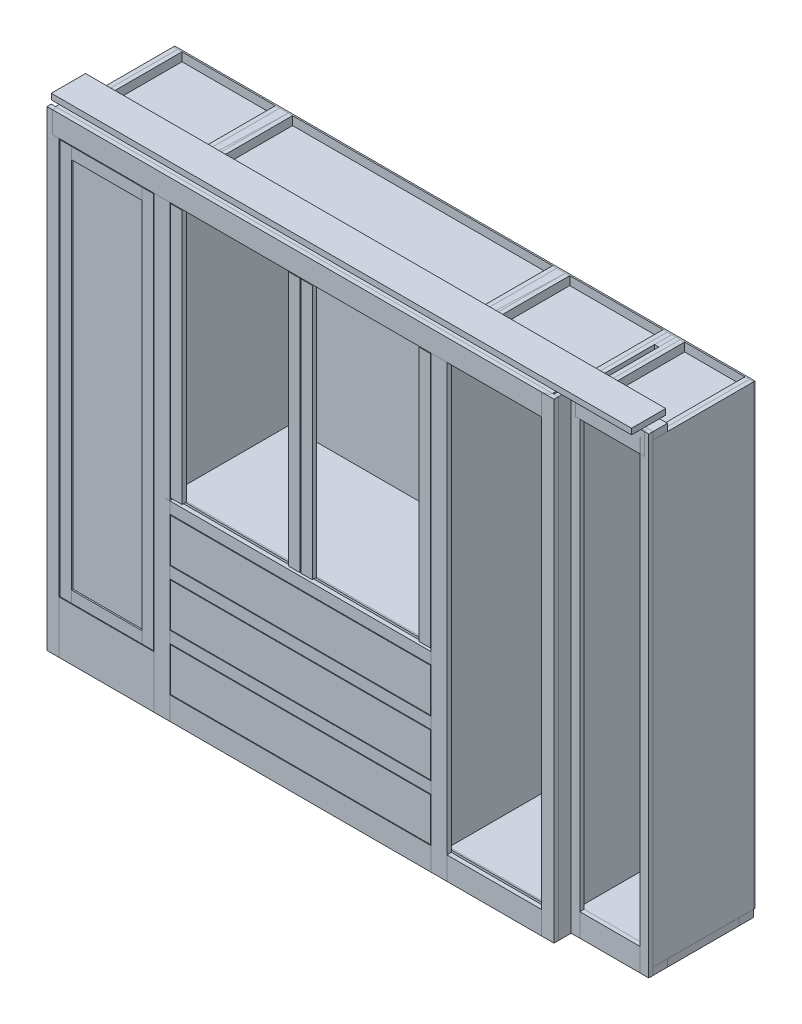
SolidWorks part; units mm, degrees
ref_plane "Front Plane" through (0, 0, 0) normal (0, 0, 1) x (1, 0, 0)
ref_plane "Top Plane" through (0, 0, 0) normal (0, 1, 0) x (1, 0, 0)
ref_plane "Right Plane" through (0, 0, 0) normal (1, 0, 0) x (0, 0, -1)
sketch "Sketch1" plane through (0, 0, 0) normal (0, 0, 1) x (1, 0, 0)
  line L0 (0, 0) -> (0, 1028.7) construction
  line L2 (-254, 19.05) -> (254, 19.05) construction
  line L3 (-254, 19.05) -> (-254, 2038.35) construction
  line L4 (-254, 2038.35) -> (254, 2038.35) construction
  line L5 (254, 19.05) -> (254, 2038.35) construction
  line L6 (-254, 19.05) -> (254, 2038.35) construction
  line L7 (-254, 2038.35) -> (254, 19.05) construction
  line L8 (-254, 2038.35) -> (-234.95, 2038.35)
  line L9 (-254, 2038.35) -> (-254, 19.05)
  line L10 (-254, 19.05) -> (-234.95, 19.05)
  line L11 (-234.95, 2038.35) -> (-234.95, 19.05)
  line L12 (254, 2038.35) -> (215.9, 2038.35)
  line L13 (254, 2038.35) -> (254, 19.05)
  line L14 (254, 19.05) -> (215.9, 19.05)
  line L15 (215.9, 2038.35) -> (215.9, 19.05)
  dimension "D1" = 19.05
  dimension "D3" = 508
  dimension "D4" = 19.05
  dimension "D2" = 2019.3
  dimension "D5" = 38.1
extrude "Boss-Extrude1" add sketch "Sketch1" against normal blind 520.7
sketch "Sketch2" plane through (0, 0, -520.7) normal (0, 0, -1) x (-1, 0, 0)
  line L1 (-215.9, 209.55) -> (-196.85, 209.55)
  line L2 (-215.9, 209.55) -> (-215.9, 19.05)
  line L3 (-215.9, 19.05) -> (-196.85, 19.05)
  line L4 (-196.85, 209.55) -> (-196.85, 19.05)
  line L6 (234.95, 19.05) -> (215.9, 19.05)
  line L7 (234.95, 19.05) -> (234.95, 209.55)
  line L8 (234.95, 209.55) -> (215.9, 209.55)
  line L9 (215.9, 19.05) -> (215.9, 209.55)
  dimension "D1" = 190.5
  dimension "D2" = 19.05
extrude "Boss-Extrude2" add sketch "Sketch2" against normal up to surface (520.7 mm away) separate body up to face at (-244.475, 1028.7, 0)
sketch "Sketch4" plane through (0, 0, -520.7) normal (0, 0, 1) x (1, 0, 0)
  line L1 (215.9, 209.55) -> (-234.95, 209.55)
  line L2 (215.9, 209.55) -> (215.9, 228.6)
  line L3 (215.9, 228.6) -> (-234.95, 228.6)
  line L4 (-234.95, 209.55) -> (-234.95, 228.6)
  dimension "D1" = 19.05
extrude "Boss-Extrude4" add sketch "Sketch4" along normal offset from surface (514.35 mm away) 6.35 separate body up to face at (-244.475, 1028.7, 0)
sketch "Sketch5" plane through (0, 0, -520.7) normal (0, 0, 1) x (1, 0, 0)
  line L1 (215.9, 2038.35) -> (196.85, 2038.35)
  line L2 (215.9, 2038.35) -> (215.9, 2000.25)
  line L3 (215.9, 2000.25) -> (196.85, 2000.25)
  line L4 (196.85, 2038.35) -> (196.85, 2000.25)
  line L5 (-234.95, 2038.35) -> (-215.9, 2038.35)
  line L6 (-234.95, 2038.35) -> (-234.95, 2000.25)
  line L7 (-234.95, 2000.25) -> (-215.9, 2000.25)
  line L8 (-215.9, 2038.35) -> (-215.9, 2000.25)
  dimension "D1" = 19.05
  dimension "D2" = 38.1
extrude "Boss-Extrude5" add sketch "Sketch5" along normal up to surface (520.7 mm away) separate body up to face at (234.95, 1028.7, 0)
sketch "Sketch6" plane through (0, 0, -520.7) normal (0, 0, 1) x (1, 0, 0)
  line L1 (-234.95, 2000.25) -> (215.9, 2000.25)
  line L2 (-234.95, 2000.25) -> (-234.95, 1981.2)
  line L3 (-234.95, 1981.2) -> (215.9, 1981.2)
  line L4 (215.9, 2000.25) -> (215.9, 1981.2)
  dimension "D1" = 19.05
extrude "Boss-Extrude6" add sketch "Sketch6" along normal up to surface (520.7 mm away) separate body up to face at (234.95, 1028.7, 0)
sketch "Sketch61" plane through (0, 0, 0) normal (0, 0, 1) x (1, 0, 0)
  line L0 (215.9, 19.05) -> (254, 19.05) construction
  line L1 (215.9, 2038.35) -> (234.95, 2038.35)
  line L2 (215.9, 2038.35) -> (215.9, 19.05)
  line L3 (215.9, 19.05) -> (234.95, 19.05)
  line L4 (234.95, 2038.35) -> (234.95, 19.05)
extrude "Boss-Extrude48" add sketch "Sketch61" against normal up to next (520.7 mm away) separate body
sketch "Sketch64" plane through (0, 0, -6.35) normal (0, 0, 1) x (1, 0, 0)
  line L0 (215.9, 209.55) -> (-234.95, 209.55) construction
  line L1 (-234.95, 228.6) -> (215.9, 228.6)
  line L2 (-234.95, 228.6) -> (-234.95, 209.55)
  line L3 (-234.95, 209.55) -> (215.9, 209.55)
  line L4 (215.9, 228.6) -> (215.9, 209.55)
extrude "Boss-Extrude50" add sketch "Sketch64" along normal blind 6.35 separate body
sketch "Sketch8" plane through (0, 0, 0) normal (0, 0, 1) x (1, 0, 0)
  line L0 (1695.45, 0) -> (1695.45, 1028.7) construction
  line L1 (254, 19.05) -> (254, 2038.35) construction
  line L2 (1949.45, 19.05) -> (1441.45, 19.05) construction
  line L3 (1949.45, 19.05) -> (1949.45, 2038.35) construction
  line L4 (1949.45, 2038.35) -> (1441.45, 2038.35) construction
  line L5 (1441.45, 19.05) -> (1441.45, 2038.35) construction
  line L6 (1949.45, 19.05) -> (1441.45, 2038.35) construction
  line L7 (1949.45, 2038.35) -> (1441.45, 19.05) construction
  line L8 (3142.9795, 0) -> (-520.5672, 0) construction
  line L10 (1949.45, 2038.35) -> (1930.4, 2038.35)
  line L11 (1949.45, 2038.35) -> (1949.45, 19.05)
  line L12 (1949.45, 19.05) -> (1930.4, 19.05)
  line L13 (1930.4, 2038.35) -> (1930.4, 19.05)
  line L14 (1441.45, 2038.35) -> (1479.55, 2038.35)
  line L15 (1441.45, 2038.35) -> (1441.45, 19.05)
  line L16 (1441.45, 19.05) -> (1479.55, 19.05)
  line L17 (1479.55, 2038.35) -> (1479.55, 19.05)
  dimension "D1" = 19.05
  dimension "D2" = 508
  dimension "D4" = 2019.3
  dimension "D5" = 19.05
  dimension "D3" = 1187.45
  dimension "D6" = 38.1
extrude "Boss-Extrude7" add sketch "Sketch8" against normal blind 520.7 separate body
sketch "Sketch10" plane through (0, 0, -520.7) normal (0, 0, -1) x (-1, 0, 0)
  line L1 (-1498.6, 19.05) -> (-1479.55, 19.05)
  line L2 (-1498.6, 19.05) -> (-1498.6, 79.375)
  line L3 (-1498.6, 79.375) -> (-1479.55, 79.375)
  line L4 (-1479.55, 19.05) -> (-1479.55, 79.375)
  line L5 (-1911.35, 19.05) -> (-1930.4, 19.05)
  line L6 (-1911.35, 19.05) -> (-1911.35, 79.375)
  line L7 (-1911.35, 79.375) -> (-1930.4, 79.375)
  line L8 (-1930.4, 19.05) -> (-1930.4, 79.375)
  dimension "D1" = 19.05
  dimension "D2" = 60.325
  dimension "D3" = 19.05
extrude "Boss-Extrude8" add sketch "Sketch10" against normal up to surface (520.7 mm away) separate body up to face at (1939.925, 1028.7, 0)
sketch "Sketch12" plane through (0, 0, -520.7) normal (0, 0, -1) x (-1, 0, 0)
  line L1 (-1498.6, 2038.35) -> (-1479.55, 2038.35)
  line L2 (-1498.6, 2038.35) -> (-1498.6, 2000.25)
  line L3 (-1498.6, 2000.25) -> (-1479.55, 2000.25)
  line L4 (-1479.55, 2038.35) -> (-1479.55, 2000.25)
  line L5 (-1911.35, 2038.35) -> (-1930.4, 2038.35)
  line L6 (-1911.35, 2038.35) -> (-1911.35, 2000.25)
  line L7 (-1911.35, 2000.25) -> (-1930.4, 2000.25)
  line L8 (-1930.4, 2038.35) -> (-1930.4, 2000.25)
  dimension "D1" = 19.05
  dimension "D4" = 19.05
  dimension "D2" = 38.1
  dimension "D3" = 38.1
extrude "Boss-Extrude9" add sketch "Sketch12" against normal up to surface (520.7 mm away) separate body up to face at (1939.925, 1028.7, 0)
sketch "Sketch13" plane through (0, 0, -520.7) normal (0, 0, -1) x (-1, 0, 0)
  line L0 (-1930.4, 2038.35) -> (-1930.4, 19.05) construction
  line L1 (-1479.55, 79.375) -> (-1930.4, 79.375)
  line L2 (-1479.55, 79.375) -> (-1479.55, 98.425)
  line L3 (-1479.55, 98.425) -> (-1930.4, 98.425)
  line L4 (-1930.4, 79.375) -> (-1930.4, 98.425)
  dimension "D1" = 19.05
extrude "Boss-Extrude10" add sketch "Sketch13" against normal offset from surface (514.35 mm away) 6.35 separate body up to face at (1460.5, 1028.7, 0)
sketch "Sketch14" plane through (0, 0, -520.7) normal (0, 0, -1) x (-1, 0, 0)
  line L0 (-1930.4, 2038.35) -> (-1930.4, 19.05) construction
  line L1 (-1479.55, 2000.25) -> (-1930.4, 2000.25)
  line L2 (-1479.55, 2000.25) -> (-1479.55, 1981.2)
  line L3 (-1479.55, 1981.2) -> (-1930.4, 1981.2)
  line L4 (-1930.4, 2000.25) -> (-1930.4, 1981.2)
  dimension "D1" = 19.05
extrude "Boss-Extrude11" add sketch "Sketch14" against normal up to surface (520.7 mm away) separate body up to face at (1939.925, 1028.7, 0)
sketch "Sketch66" plane through (0, 0, -6.35) normal (0, 0, 1) x (1, 0, 0)
  line L0 (1930.4, 79.375) -> (1479.55, 79.375) construction
  line L1 (1479.55, 98.425) -> (1930.4, 98.425)
  line L2 (1479.55, 98.425) -> (1479.55, 79.375)
  line L3 (1479.55, 79.375) -> (1930.4, 79.375)
  line L4 (1930.4, 98.425) -> (1930.4, 79.375)
extrude "Boss-Extrude52" add sketch "Sketch66" along normal blind 6.35 separate body
sketch "Sketch69" plane through (0, 0, 0) normal (0, 0, 1) x (1, 0, 0)
  line L1 (1479.55, 2038.35) -> (1460.5, 2038.35)
  line L2 (1479.55, 2038.35) -> (1479.55, 19.05)
  line L3 (1479.55, 19.05) -> (1460.5, 19.05)
  line L4 (1460.5, 2038.35) -> (1460.5, 19.05)
extrude "Boss-Extrude55" add sketch "Sketch69" against normal up to next (520.7 mm away) separate body
sketch "Sketch15" plane through (0, 0, -520.7) normal (0, 0, -1) x (-1, 0, 0)
  line L1 (-254, 19.05) -> (-273.05, 19.05)
  line L2 (-254, 19.05) -> (-254, 69.85)
  line L3 (-254, 69.85) -> (-273.05, 69.85)
  line L4 (-273.05, 19.05) -> (-273.05, 69.85)
  line L5 (-1441.45, 19.05) -> (-1422.4, 19.05)
  line L6 (-1441.45, 19.05) -> (-1441.45, 69.85)
  line L7 (-1441.45, 69.85) -> (-1422.4, 69.85)
  line L8 (-1422.4, 19.05) -> (-1422.4, 69.85)
  line L9 (-1441.45, 2038.35) -> (-1422.4, 2038.35)
  line L10 (-1441.45, 2038.35) -> (-1441.45, 2000.25)
  line L11 (-1441.45, 2000.25) -> (-1422.4, 2000.25)
  line L12 (-1422.4, 2038.35) -> (-1422.4, 2000.25)
  line L13 (-254, 2038.35) -> (-273.05, 2038.35)
  line L14 (-254, 2038.35) -> (-254, 2000.25)
  line L15 (-254, 2000.25) -> (-273.05, 2000.25)
  line L16 (-273.05, 2038.35) -> (-273.05, 2000.25)
  dimension "D1" = 19.05
  dimension "D2" = 38.1
  dimension "D3" = 50.8
extrude "Boss-Extrude12" add sketch "Sketch15" against normal up to surface (520.7 mm away) separate body up to face at (1460.5, 1028.7, 0)
sketch "Sketch16" plane through (0, 0, -520.7) normal (0, 0, -1) x (-1, 0, 0)
  line L0 (-254, 19.05) -> (-254, 2038.35) construction
  line L1 (-1441.45, 2000.25) -> (-254, 2000.25)
  line L2 (-1441.45, 2000.25) -> (-1441.45, 1981.2)
  line L3 (-1441.45, 1981.2) -> (-254, 1981.2)
  line L4 (-254, 2000.25) -> (-254, 1981.2)
  line L6 (-1441.45, 69.85) -> (-254, 69.85)
  line L7 (-1441.45, 69.85) -> (-1441.45, 88.9)
  line L8 (-1441.45, 88.9) -> (-254, 88.9)
  line L9 (-254, 69.85) -> (-254, 88.9)
  dimension "D1" = 19.05
  dimension "D2" = 19.05
extrude "Boss-Extrude13" add sketch "Sketch16" against normal up to surface (520.7 mm away) separate body up to face at (1460.5, 1028.7, 0)
sketch "Sketch17" plane through (0, 0, -520.7) normal (0, 0, -1) x (-1, 0, 0)
  line L0 (-254, 19.05) -> (-254, 2038.35) construction
  line L1 (-1441.45, 1981.2) -> (-254, 1981.2) construction
  line L2 (-1441.45, 1981.2) -> (-1441.45, 841.375) construction
  line L3 (-1441.45, 841.375) -> (-254, 841.375) construction
  line L4 (-254, 1981.2) -> (-254, 841.375) construction
  line L6 (-1441.45, 841.375) -> (-254, 841.375)
  line L7 (-1441.45, 841.375) -> (-1441.45, 822.325)
  line L8 (-1441.45, 822.325) -> (-254, 822.325)
  line L9 (-254, 841.375) -> (-254, 822.325)
  line L10 (-254, 88.9) -> (-1441.45, 88.9) construction
  dimension "D2" = 19.05
  dimension "D1" = 733.425
extrude "Boss-Extrude14" add sketch "Sketch17" against normal offset from surface (514.35 mm away) 6.35 separate body up to face at (234.95, 1028.7, 0)
sketch "Sketch65" plane through (0, 0, -6.35) normal (0, 0, 1) x (1, 0, 0)
  line L0 (1441.45, 822.325) -> (1441.45, 841.375) construction
  line L1 (254, 841.375) -> (1441.45, 841.375)
  line L2 (254, 841.375) -> (254, 822.325)
  line L3 (254, 822.325) -> (1441.45, 822.325)
  line L4 (1441.45, 841.375) -> (1441.45, 822.325)
  line L5 (254, 822.325) -> (1441.45, 822.325) construction
extrude "Boss-Extrude51" add sketch "Sketch65" along normal blind 6.35 separate body
sketch "Sketch67" plane through (0, 0, 0) normal (0, 0, 1) x (1, 0, 0)
  line L1 (254, 2038.35) -> (234.95, 2038.35)
  line L2 (254, 2038.35) -> (254, 19.05)
  line L3 (254, 19.05) -> (234.95, 19.05)
  line L4 (234.95, 2038.35) -> (234.95, 19.05)
extrude "Boss-Extrude53" add sketch "Sketch67" against normal up to next (520.7 mm away) separate body
sketch "Sketch68" plane through (0, 0, 0) normal (0, 0, 1) x (1, 0, 0)
  line L0 (1441.45, 19.05) -> (1479.55, 19.05) construction
  line L1 (1441.45, 2038.35) -> (1460.5, 2038.35)
  line L2 (1441.45, 2038.35) -> (1441.45, 19.05)
  line L3 (1441.45, 19.05) -> (1460.5, 19.05)
  line L4 (1460.5, 2038.35) -> (1460.5, 19.05)
extrude "Boss-Extrude54" add sketch "Sketch68" against normal up to next (520.7 mm away) separate body
sketch "Sketch25" plane through (0, 0, -520.7) normal (0, 0, -1) x (-1, 0, 0)
  line L0 (-1949.45, 19.05) -> (-1949.45, 2038.35) construction
  line L1 (-1968.5, 2038.35) -> (-1987.55, 2038.35)
  line L2 (-1968.5, 2038.35) -> (-1968.5, 19.05)
  line L3 (-1968.5, 19.05) -> (-1987.55, 19.05)
  line L4 (-1987.55, 2038.35) -> (-1987.55, 19.05)
  line L5 (-1949.45, 2038.35) -> (-1930.4, 2038.35) construction
  dimension "D1" = 19.05
  dimension "D2" = 19.05
extrude "Boss-Extrude22" add sketch "Sketch25" against normal blind 444.5 separate body
sketch "Sketch26" plane through (0, 0, -520.7) normal (0, 0, 1) x (1, 0, 0)
  line L1 (1987.55, 2038.35) -> (2311.4, 2038.35) construction
  line L2 (1987.55, 2038.35) -> (1987.55, 19.05) construction
  line L3 (1987.55, 19.05) -> (2311.4, 19.05) construction
  line L4 (2311.4, 2038.35) -> (2311.4, 19.05) construction
  line L5 (2311.4, 2038.35) -> (2292.35, 2038.35)
  line L6 (2311.4, 2038.35) -> (2311.4, 19.05)
  line L7 (2311.4, 19.05) -> (2292.35, 19.05)
  line L8 (2292.35, 2038.35) -> (2292.35, 19.05)
  dimension "D3" = 19.05
  dimension "D2" = 2019.3
  dimension "D1" = 323.85
extrude "Boss-Extrude23" add sketch "Sketch26" along normal blind 444.5 separate body
sketch "Sketch27" plane through (0, 0, -520.7) normal (0, 0, -1) x (-1, 0, 0)
  line L1 (-1987.55, 2038.35) -> (-2006.6, 2038.35)
  line L2 (-1987.55, 2038.35) -> (-1987.55, 2000.25)
  line L3 (-1987.55, 2000.25) -> (-2006.6, 2000.25)
  line L4 (-2006.6, 2038.35) -> (-2006.6, 2000.25)
  line L5 (-2292.35, 2038.35) -> (-2273.3, 2038.35)
  line L6 (-2292.35, 2038.35) -> (-2292.35, 2000.25)
  line L7 (-2292.35, 2000.25) -> (-2273.3, 2000.25)
  line L8 (-2273.3, 2038.35) -> (-2273.3, 2000.25)
  line L9 (-1987.55, 19.05) -> (-2006.6, 19.05)
  line L10 (-1987.55, 19.05) -> (-1987.55, 69.85)
  line L11 (-1987.55, 69.85) -> (-2006.6, 69.85)
  line L12 (-2006.6, 19.05) -> (-2006.6, 69.85)
  line L13 (-2292.35, 19.05) -> (-2273.3, 19.05)
  line L14 (-2292.35, 19.05) -> (-2292.35, 69.85)
  line L15 (-2292.35, 69.85) -> (-2273.3, 69.85)
  line L16 (-2273.3, 19.05) -> (-2273.3, 69.85)
  dimension "D1" = 19.05
  dimension "D2" = 38.1
  dimension "D3" = 50.8
extrude "Boss-Extrude24" add sketch "Sketch27" against normal up to surface (444.5 mm away) separate body up to face at (2301.875, 1028.7, -76.2)
sketch "Sketch28" plane through (0, 0, -520.7) normal (0, 0, -1) x (-1, 0, 0)
  line L0 (-2292.35, 2038.35) -> (-2292.35, 19.05) construction
  line L1 (-1987.55, 69.85) -> (-2292.35, 69.85)
  line L2 (-1987.55, 69.85) -> (-1987.55, 88.9)
  line L3 (-1987.55, 88.9) -> (-2292.35, 88.9)
  line L4 (-2292.35, 69.85) -> (-2292.35, 88.9)
  line L6 (-1987.55, 2000.25) -> (-2292.35, 2000.25)
  line L7 (-1987.55, 2000.25) -> (-1987.55, 1981.2)
  line L8 (-1987.55, 1981.2) -> (-2292.35, 1981.2)
  line L9 (-2292.35, 2000.25) -> (-2292.35, 1981.2)
  dimension "D1" = 19.05
extrude "Boss-Extrude25" add sketch "Sketch28" against normal up to surface (444.5 mm away) separate body up to face at (2301.875, 1028.7, -76.2)
sketch "Sketch20" plane through (0, 0, 0) normal (0, 0, 1) x (1, 0, 0)
  line L1 (-254, 2038.35) -> (-273.05, 2038.35)
  line L2 (-254, 2038.35) -> (-254, 19.05)
  line L3 (-254, 19.05) -> (-273.05, 19.05)
  line L4 (-273.05, 2038.35) -> (-273.05, 19.05)
  dimension "D1" = 19.05
extrude "Boss-Extrude17" add sketch "Sketch20" against normal blind 63.5 separate body
sketch "Sketch21" plane through (0, 0, 0) normal (0, 0, 1) x (1, 0, 0)
  line L0 (-234.95, 19.05) -> (-234.95, 2038.35) construction
  line L1 (-219.075, 2070.1) -> (-273.05, 2070.1)
  line L2 (-219.075, 2070.1) -> (-219.075, -12.7)
  line L3 (-219.075, -12.7) -> (-273.05, -12.7)
  line L4 (-273.05, 2070.1) -> (-273.05, -12.7)
  line L8 (-254, 19.05) -> (-234.95, 19.05) construction
  line L9 (-234.95, 2038.35) -> (-215.9, 2038.35) construction
  dimension "D1" = 15.875
  dimension "D2" = 53.975
  dimension "D3" = 31.75
  dimension "D4" = 31.75
extrude "Boss-Extrude18" add sketch "Sketch21" along normal blind 19.05 separate body
sketch "Sketch22" plane through (0, 0, 0) normal (0, 0, 1) x (1, 0, 0)
  line L0 (234.95, 1959.776) -> (234.95, 1827.9449) construction
  line L1 (254, 2038.35) -> (215.9, 2038.35) construction
  line L2 (1460.5, 2082.8) -> (1460.5, -47917.2) construction
  line L3 (1479.55, 2038.35) -> (1441.45, 2038.35) construction
  line L4 (1949.45, 2082.8) -> (1949.45, 52082.8) construction
  line L5 (1930.4, 2038.35) -> (1930.4, 19.05) construction
  line L6 (-219.075, -12.7) -> (-219.075, 2070.1) construction
  line L7 (200.025, -12.7) -> (269.875, -12.7)
  line L8 (200.025, -12.7) -> (200.025, 2070.1)
  line L9 (200.025, 2070.1) -> (269.875, 2070.1)
  line L10 (269.875, -12.7) -> (269.875, 2070.1)
  line L11 (200.025, -12.7) -> (269.875, 2070.1) construction
  line L12 (200.025, 2070.1) -> (269.875, -12.7) construction
  line L13 (1425.575, -12.7) -> (1495.425, -12.7)
  line L14 (1425.575, -12.7) -> (1425.575, 2070.1)
  line L15 (1425.575, 2070.1) -> (1495.425, 2070.1)
  line L16 (1495.425, -12.7) -> (1495.425, 2070.1)
  line L17 (1425.575, -12.7) -> (1495.425, 2070.1) construction
  line L18 (1425.575, 2070.1) -> (1495.425, -12.7) construction
  line L19 (1914.525, -12.7) -> (1968.5, -12.7)
  line L20 (1914.525, -12.7) -> (1914.525, 2070.1)
  line L21 (1914.525, 2070.1) -> (1968.5, 2070.1)
  line L22 (1968.5, -12.7) -> (1968.5, 2070.1)
  line L23 (1914.525, -12.7) -> (1968.5, 2070.1) construction
  line L24 (1914.525, 2070.1) -> (1968.5, -12.7) construction
  line L27 (215.9, 19.05) -> (254, 19.05) construction
  line L28 (1949.45, 19.05) -> (1949.45, 2038.35) construction
  line L29 (1930.4, 2038.35) -> (1911.35, 2038.35) construction
  point P6 (1460.5, 2038.35)
  point P12 (234.95, 1028.7)
  point P17 (1460.5, 1028.7)
  point P22 (1941.5125, 1028.7)
  point P27 (234.95, 2038.35)
  dimension "D1" = 69.85
  dimension "D3" = 31.75
  dimension "D5" = 31.75
  dimension "D4" = 15.875
  dimension "D6" = 53.975
extrude "Boss-Extrude19" add sketch "Sketch22" along normal blind 19.05 separate body
sketch "Sketch23" plane through (0, 0, 0) normal (0, 0, 1) x (1, 0, 0)
  line L1 (-246.1329, -12.7) -> (234.95, -12.7)
  line L2 (-246.1329, -12.7) -> (-246.1329, 219.075)
  line L3 (-246.1329, 219.075) -> (234.95, 219.075)
  line L4 (234.95, -12.7) -> (234.95, 219.075)
  line L5 (-234.95, 228.6) -> (215.9, 228.6) construction
  line L8 (200.025, -12.7) -> (269.875, -12.7) construction
  dimension "D1" = 9.525
extrude "Boss-Extrude20" add sketch "Sketch23" along normal blind 19.05 separate body
sketch "Sketch24" plane through (0, 0, 0) normal (0, 0, 1) x (1, 0, 0)
  line L0 (200.025, -12.7) -> (269.875, -12.7) construction
  line L1 (234.95, -12.7) -> (1949.45, -12.7)
  line L2 (234.95, -12.7) -> (234.95, 88.9)
  line L3 (234.95, 88.9) -> (1949.45, 88.9)
  line L4 (1949.45, -12.7) -> (1949.45, 88.9)
  line L5 (1949.45, 19.05) -> (1949.45, 2038.35) construction
  line L6 (863.6, -193.55) -> (863.6, 49806.45) construction
  line L7 (1941.5125, 1974.85) -> (-248.3733, 1974.85)
  line L8 (1941.5125, 1974.85) -> (1941.5125, 2070.1)
  line L9 (1941.5125, 2070.1) -> (-248.3733, 2070.1)
  line L10 (-248.3733, 1974.85) -> (-248.3733, 2070.1)
  line L11 (1968.5, 2070.1) -> (1914.525, 2070.1) construction
  line L12 (-746, 723.9) -> (49254, 723.9) construction
  line L13 (1479.55, 1981.2) -> (1930.4, 1981.2) construction
  line L15 (1460.5, 1082.8) -> (1460.5, 51082.8) construction
  line L16 (234.95, 781.05) -> (1460.5, 781.05)
  line L17 (234.95, 781.05) -> (234.95, 831.85)
  line L18 (234.95, 831.85) -> (1460.5, 831.85)
  line L19 (1460.5, 781.05) -> (1460.5, 831.85)
  line L20 (234.95, 781.05) -> (1460.5, 831.85) construction
  line L21 (234.95, 831.85) -> (1460.5, 781.05) construction
  line L22 (1479.55, 2038.35) -> (1441.45, 2038.35) construction
  line L23 (234.95, 1082.8) -> (234.95, 51082.8) construction
  line L24 (254, 2038.35) -> (215.9, 2038.35) construction
  point P12 (1941.5125, 2070.1)
  point P21 (602.7923, 796.2974)
  point P35 (1460.5, 2038.35)
  point P40 (234.95, 2038.35)
  dimension "D1" = 101.6
  dimension "D2" = 0
  dimension "D3" = 95.25
  dimension "D4" = 50.8
  dimension "D6" = 6.35
  dimension "D7" = 692.15
extrude "Boss-Extrude21" add sketch "Sketch24" along normal blind 19.05 separate body
sketch "Sketch29" plane through (0, 0, -76.2) normal (0, 0, 1) x (1, 0, 0)
  line L0 (1914.525, -12.7) -> (1968.5, -12.7) construction
  line L1 (1941.5125, 2070.1) -> (-248.3733, 2070.1) construction
  line L6 (2311.4, 2070.1) -> (2273.3, 2070.1)
  line L7 (2311.4, 2070.1) -> (2311.4, -12.7)
  line L8 (2311.4, -12.7) -> (2273.3, -12.7)
  line L9 (2273.3, 2070.1) -> (2273.3, -12.7)
  line L10 (1968.5, 2070.1) -> (2006.6, 2070.1)
  line L11 (1968.5, 2070.1) -> (1968.5, -12.7)
  line L12 (1968.5, -12.7) -> (2006.6, -12.7)
  line L13 (2006.6, 2070.1) -> (2006.6, -12.7)
  dimension "D1" = 38.1
extrude "Boss-Extrude26" add sketch "Sketch29" along normal blind 19.05 separate body
sketch "Sketch30" plane through (0, 0, -76.2) normal (0, 0, 1) x (1, 0, 0)
  line L0 (2292.35, 1981.2) -> (1987.55, 1981.2) construction
  line L1 (1987.55, 1974.85) -> (2292.35, 1974.85)
  line L2 (1987.55, 1974.85) -> (1987.55, 2070.1)
  line L3 (1987.55, 2070.1) -> (2292.35, 2070.1)
  line L4 (2292.35, 1974.85) -> (2292.35, 2070.1)
  line L5 (1987.55, 88.9) -> (2292.35, 88.9)
  line L6 (1987.55, 88.9) -> (1987.55, -12.7)
  line L7 (1987.55, -12.7) -> (2292.35, -12.7)
  line L8 (2292.35, 88.9) -> (2292.35, -12.7)
  line L11 (2273.3, -12.7) -> (2311.4, -12.7) construction
  line L12 (2006.6, 2070.1) -> (1968.5, 2070.1) construction
  line L13 (2311.4, 2070.1) -> (2273.3, 2070.1) construction
  point P17 (2292.35, -12.7)
  point P21 (1987.55, 2070.1)
  point P22 (2292.35, 2070.1)
  dimension "D3" = 6.35
extrude "Boss-Extrude27" add sketch "Sketch30" along normal blind 19.05 separate body
sketch "Sketch33" plane through (0, 0, 0) normal (0, 0, 1) x (1, 0, 0)
  line L0 (-248.3733, 1974.85) -> (1941.5125, 1974.85) construction
  line L1 (-219.075, 1974.85) -> (200.025, 1974.85) construction
  line L2 (-219.075, 1974.85) -> (-219.075, 219.075) construction
  line L3 (-219.075, 219.075) -> (200.025, 219.075) construction
  line L4 (200.025, 1974.85) -> (200.025, 219.075) construction
  line L5 (-219.075, -12.7) -> (-219.075, 2070.1) construction
  line L6 (200.025, 2070.1) -> (200.025, -12.7) construction
  line L7 (234.95, 219.075) -> (-246.1329, 219.075) construction
  line L8 (-215.9, 1971.675) -> (196.85, 1971.675) construction
  line L9 (196.85, 1971.675) -> (196.85, 222.25) construction
  line L10 (-215.9, 222.25) -> (196.85, 222.25) construction
  line L11 (-215.9, 1971.675) -> (-215.9, 222.25) construction
  line L13 (-215.9, 1971.675) -> (-165.1, 1971.675)
  line L14 (-215.9, 1971.675) -> (-215.9, 222.25)
  line L15 (-215.9, 222.25) -> (-165.1, 222.25)
  line L16 (-165.1, 1971.675) -> (-165.1, 222.25)
  line L17 (196.85, 222.25) -> (146.05, 222.25)
  line L18 (196.85, 222.25) -> (196.85, 1971.675)
  line L19 (196.85, 1971.675) -> (146.05, 1971.675)
  line L20 (146.05, 222.25) -> (146.05, 1971.675)
  dimension "D2" = 50.8
  dimension "D1" = 3.175
extrude "Boss-Extrude29" add sketch "Sketch33" along normal blind 19.05 separate body
sketch "Sketch34" plane through (0, 0, 0) normal (0, 0, 1) x (1, 0, 0)
  line L0 (146.05, 222.25) -> (196.85, 222.25) construction
  line L1 (-177.8, 1971.675) -> (158.75, 1971.675)
  line L2 (-177.8, 1971.675) -> (-177.8, 1920.875)
  line L3 (-177.8, 1920.875) -> (158.75, 1920.875)
  line L4 (158.75, 1971.675) -> (158.75, 1920.875)
  line L6 (-177.8, 222.25) -> (158.75, 222.25)
  line L7 (-177.8, 222.25) -> (-177.8, 273.05)
  line L8 (-177.8, 273.05) -> (158.75, 273.05)
  line L9 (158.75, 222.25) -> (158.75, 273.05)
  line L10 (-165.1, 222.25) -> (-165.1, 1971.675) construction
  line L11 (146.05, 1971.675) -> (146.05, 222.25) construction
  line L12 (-165.1, 1971.675) -> (-215.9, 1971.675) construction
  dimension "D1" = 50.8
  dimension "D2" = 12.7
  dimension "D3" = 12.7
extrude "Boss-Extrude30" add sketch "Sketch34" along normal blind 19.05 separate body
sketch "Sketch36" plane through (0, 1971.675, 0) normal (0, 1, 0) x (1, 0, 0)
  line L0 (-165.1, -19.05) -> (-165.1, 0) construction
  line L1 (-165.1, -6.35) -> (-177.8, -6.35)
  line L2 (-165.1, -6.35) -> (-165.1, -12.7)
  line L3 (-165.1, -12.7) -> (-177.8, -12.7)
  line L4 (-177.8, -6.35) -> (-177.8, -12.7)
  line L5 (-1168.275, -9.525) -> (48831.725, -9.525) construction
  line L6 (-9.525, -19.05) -> (-9.525, 0) construction
  line L7 (158.75, -19.05) -> (-177.8, -19.05) construction
  line L8 (158.75, 0) -> (-177.8, 0) construction
  line L9 (158.75, -6.35) -> (158.75, -12.7)
  line L10 (146.05, -12.7) -> (158.75, -12.7)
  line L11 (146.05, -6.35) -> (146.05, -12.7)
  line L12 (146.05, -6.35) -> (158.75, -6.35)
  point P9 (-165.1, -9.525)
  dimension "D2" = 12.7
  dimension "D1" = 6.35
extrude "Cut-Extrude1" cut sketch "Sketch36" against normal through all
sketch "Sketch37" plane through (0, 1971.675, 0) normal (0, 1, 0) x (1, 0, 0)
  line L1 (-165.1, -6.35) -> (-177.8, -6.35)
  line L2 (-165.1, -6.35) -> (-165.1, 0)
  line L3 (-165.1, 0) -> (-177.8, 0)
  line L4 (-177.8, -6.35) -> (-177.8, 0)
  line L6 (-165.1, -12.7) -> (-177.8, -12.7)
  line L7 (-165.1, -12.7) -> (-165.1, -19.05)
  line L8 (-165.1, -19.05) -> (-177.8, -19.05)
  line L9 (-177.8, -12.7) -> (-177.8, -19.05)
  line L10 (-177.8, -6.35) -> (-177.8, -12.7) construction
  line L12 (158.75, 0) -> (-177.8, 0) construction
  line L13 (158.75, -19.05) -> (-177.8, -19.05) construction
  line L14 (-9.525, -19.05) -> (-9.525, 0) construction
  line L15 (158.75, -12.7) -> (158.75, -19.05)
  line L16 (146.05, -19.05) -> (158.75, -19.05)
  line L17 (146.05, -12.7) -> (146.05, -19.05)
  line L18 (146.05, -12.7) -> (158.75, -12.7)
  line L19 (158.75, -6.35) -> (158.75, 0)
  line L20 (146.05, 0) -> (158.75, 0)
  line L21 (146.05, -6.35) -> (146.05, 0)
  line L22 (146.05, -6.35) -> (158.75, -6.35)
extrude "Cut-Extrude2" cut sketch "Sketch37" against normal through all
sketch "Sketch39" plane through (-177.8, 0, 0) normal (-1, 0, 0) x (0, 0, 1)
  line L0 (6.35, 1920.875) -> (6.35, 1971.675) construction
  line L1 (12.7, 1920.875) -> (6.35, 1920.875)
  line L2 (12.7, 1920.875) -> (12.7, 1933.575)
  line L3 (12.7, 1933.575) -> (6.35, 1933.575)
  line L4 (6.35, 1920.875) -> (6.35, 1933.575)
  line L5 (6.35, 222.25) -> (6.35, 273.05) construction
  line L6 (12.7, 273.05) -> (6.35, 273.05)
  line L7 (12.7, 273.05) -> (12.7, 260.35)
  line L8 (12.7, 260.35) -> (6.35, 260.35)
  line L9 (6.35, 273.05) -> (6.35, 260.35)
  dimension "D2" = 12.7
  dimension "D1" = 12.7
extrude "Cut-Extrude3" cut sketch "Sketch39" against normal through all
sketch "Sketch40" plane through (0, 0, 6.35) normal (0, 0, -1) x (-1, 0, 0)
  line L1 (177.8, 1933.575) -> (-158.75, 1933.575)
  line L2 (177.8, 1933.575) -> (177.8, 260.35)
  line L3 (177.8, 260.35) -> (-158.75, 260.35)
  line L4 (-158.75, 1933.575) -> (-158.75, 260.35)
extrude "Boss-Extrude31" add sketch "Sketch40" against normal up to surface (6.35 mm away) separate body up to face at (-9.525, 266.7, 12.7)
sketch "Sketch41" plane through (0, 0, -520.7) normal (0, 0, -1) x (-1, 0, 0)
  line L1 (254, 2038.35) -> (-2311.4, 2038.35)
  line L2 (254, 2038.35) -> (254, 19.05)
  line L3 (254, 19.05) -> (-2311.4, 19.05)
  line L4 (-2311.4, 2038.35) -> (-2311.4, 19.05)
  line L5 (-2311.4, 19.05) -> (-2311.4, 2038.35) construction
  line L6 (234.95, 2038.35) -> (254, 2038.35) construction
  line L7 (254, 2038.35) -> (254, 19.05) construction
extrude "Boss-Extrude32" add sketch "Sketch41" along normal blind 6.35 separate body
sketch "Sketch42" plane through (0, 2038.35, 0) normal (0, 1, 0) x (1, 0, 0)
  line L2 (-254, 0) -> (1943.1, 0)
  line L3 (-254, 0) -> (-254, 63.5)
  line L4 (-254, 63.5) -> (1943.1, 63.5)
  line L6 (2311.4, 76.2) -> (1447.8, 76.2)
  line L7 (2311.4, 76.2) -> (2311.4, 139.7)
  line L8 (2311.4, 139.7) -> (1447.8, 139.7)
  line L9 (1447.8, 76.2) -> (1447.8, 139.7)
  line L10 (1943.1, 0) -> (1943.1, 63.5)
  dimension "D1" = 863.6
  dimension "D2" = 2197.1
  dimension "D3" = 63.5
extrude "Boss-Extrude33" add sketch "Sketch42" along normal blind 31.75 separate body
sketch "Sketch43" plane through (0, 0, 0) normal (0, 0, 1) x (1, 0, 0)
  line L0 (269.875, -12.7) -> (269.875, 2070.1) construction
  line L1 (269.875, 1974.85) -> (1425.575, 1974.85) construction
  line L2 (269.875, 1974.85) -> (269.875, 841.375) construction
  line L3 (269.875, 841.375) -> (1425.575, 841.375) construction
  line L4 (1425.575, 1974.85) -> (1425.575, 841.375) construction
  line L5 (-248.3733, 1974.85) -> (1941.5125, 1974.85) construction
  line L6 (254, 841.375) -> (1441.45, 841.375) construction
  line L7 (1425.575, 2070.1) -> (1425.575, -12.7) construction
  line L8 (273.05, 1971.675) -> (273.05, 844.55) construction
  line L9 (273.05, 844.55) -> (1422.4, 844.55) construction
  line L10 (1422.4, 1971.675) -> (1422.4, 844.55) construction
  line L11 (273.05, 1971.675) -> (1422.4, 1971.675) construction
  line L13 (1422.4, 1971.675) -> (1371.6, 1971.675)
  line L14 (1422.4, 1971.675) -> (1422.4, 844.55)
  line L15 (1422.4, 844.55) -> (1371.6, 844.55)
  line L16 (1371.6, 1971.675) -> (1371.6, 844.55)
  line L17 (273.05, 1971.675) -> (323.85, 1971.675)
  line L18 (273.05, 1971.675) -> (273.05, 844.55)
  line L19 (273.05, 844.55) -> (323.85, 844.55)
  line L20 (323.85, 1971.675) -> (323.85, 844.55)
  dimension "D2" = 50.8
  dimension "D1" = 3.175
extrude "Boss-Extrude34" add sketch "Sketch43" along normal blind 19.05 separate body
sketch "Sketch44" plane through (0, 0, 0) normal (0, 0, 1) x (1, 0, 0)
  line L0 (847.725, -193.55) -> (847.725, 49806.45) construction
  line L1 (1460.5, 831.85) -> (234.95, 831.85) construction
  line L4 (849.3125, -193.55) -> (849.3125, 49806.45) construction
  line L5 (846.1375, -193.55) -> (846.1375, 49806.45) construction
  line L7 (323.85, 1971.675) -> (1371.6, 1971.675) construction
  line L8 (323.85, 1971.675) -> (323.85, 844.55) construction
  line L9 (323.85, 844.55) -> (1371.6, 844.55) construction
  line L10 (1371.6, 1971.675) -> (1371.6, 844.55) construction
  line L11 (846.1375, 1971.675) -> (795.3375, 1971.675)
  line L12 (846.1375, 1971.675) -> (846.1375, 844.55)
  line L13 (846.1375, 844.55) -> (795.3375, 844.55)
  line L14 (795.3375, 1971.675) -> (795.3375, 844.55)
  line L15 (849.3125, 1971.675) -> (900.1125, 1971.675)
  line L16 (849.3125, 1971.675) -> (849.3125, 844.55)
  line L17 (849.3125, 844.55) -> (900.1125, 844.55)
  line L18 (900.1125, 1971.675) -> (900.1125, 844.55)
  point P5 (847.725, 831.85)
  dimension "D3" = 50.8
extrude "Boss-Extrude35" add sketch "Sketch44" along normal blind 19.05 separate body
sketch "Sketch48" plane through (0, 0, 0) normal (0, 0, 1) x (1, 0, 0)
  line L1 (1949.45, 2070.1) -> (1968.5, 2070.1)
  line L2 (1949.45, 2070.1) -> (1949.45, -12.7)
  line L3 (1949.45, -12.7) -> (1968.5, -12.7)
  line L4 (1968.5, 2070.1) -> (1968.5, -12.7)
  dimension "D1" = 19.05
extrude "Boss-Extrude38" add sketch "Sketch48" against normal offset from surface (152.4 mm away) 76.2 separate body up to face at (1978.025, 1028.7, -76.2) offset beyond the face yes
sketch "Sketch49" plane through (0, 0, -520.7) normal (0, 0, -1) x (-1, 0, 0)
  line L0 (-2311.4, 19.05) -> (254, 19.05) construction
  line L1 (-1949.45, 2038.35) -> (-1968.5, 2038.35)
  line L2 (-1949.45, 2038.35) -> (-1949.45, 19.05)
  line L3 (-1949.45, 19.05) -> (-1968.5, 19.05)
  line L4 (-1968.5, 2038.35) -> (-1968.5, 19.05)
  line L5 (-1987.55, 19.05) -> (-1968.5, 19.05) construction
  dimension "D1" = 19.05
extrude "Boss-Extrude39" add sketch "Sketch49" against normal blind 76.2 separate body
sketch "Sketch50" plane through (0, 2070.1, 0) normal (0, 1, 0) x (1, 0, 0)
  line L0 (1949.45, 152.4) -> (1949.45, 0) construction
  line L1 (1968.5, 152.4) -> (1949.45, 152.4)
  line L2 (1968.5, 152.4) -> (1968.5, 76.2)
  line L3 (1968.5, 76.2) -> (1949.45, 76.2)
  line L4 (1949.45, 152.4) -> (1949.45, 76.2)
extrude "Cut-Extrude5" cut sketch "Sketch50" against normal up to surface (31.75 mm away) up to face at (1978.025, 2038.35, -298.45)
sketch "Sketch58" plane through (0, -12.7, 0) normal (0, -1, 0) x (1, 0, 0)
  line L0 (1968.5, -152.4) -> (1968.5, 0) construction
  line L1 (1968.5, -76.2) -> (1949.45, -76.2)
  line L2 (1968.5, -76.2) -> (1968.5, -152.4)
  line L3 (1968.5, -152.4) -> (1949.45, -152.4)
  line L4 (1949.45, -76.2) -> (1949.45, -152.4)
extrude "Cut-Extrude6" cut sketch "Sketch58" against normal up to surface (31.75 mm away) up to face at (1978.025, 19.05, -298.45)
sketch "Sketch46" plane through (0, 19.05, 0) normal (0, -1, 0) x (1, 0, 0)
  line L1 (-254, -520.7) -> (1943.1, -520.7)
  line L2 (-254, -520.7) -> (-254, -457.2)
  line L3 (-254, -457.2) -> (1943.1, -457.2)
  line L4 (1943.1, -520.7) -> (1943.1, -457.2)
  line L5 (1441.45, 0) -> (254, 0) construction
  line L6 (1943.1, 0) -> (-254, 0)
  line L7 (1943.1, 0) -> (1943.1, -63.5)
  line L8 (1943.1, -63.5) -> (-254, -63.5)
  line L9 (-254, 0) -> (-254, -63.5)
  dimension "D1" = 63.5
  dimension "D2" = 63.5
  dimension "D3" = 2197.1
extrude "Boss-Extrude36" add sketch "Sketch46" along normal blind 31.75 separate body
sketch "Sketch47" plane through (0, 19.05, 0) normal (0, -1, 0) x (1, 0, 0)
  line L0 (1943.1, -457.2) -> (-254, -457.2) construction
  line L1 (-203.2, -63.5) -> (-139.7, -63.5)
  line L2 (-203.2, -63.5) -> (-203.2, -457.2)
  line L3 (-203.2, -457.2) -> (-139.7, -457.2)
  line L4 (-139.7, -63.5) -> (-139.7, -457.2)
  line L5 (317.5, -63.5) -> (381, -63.5)
  line L6 (1943.1, -63.5) -> (1879.6, -63.5)
  line L7 (1943.1, -63.5) -> (1943.1, -457.2)
  line L8 (1943.1, -457.2) -> (1879.6, -457.2)
  line L9 (1879.6, -63.5) -> (1879.6, -457.2)
  line L10 (317.5, -63.5) -> (317.5, -457.2)
  line L11 (317.5, -457.2) -> (381, -457.2)
  line L12 (381, -63.5) -> (381, -457.2)
  line L13 (1320.8, -63.5) -> (1384.3, -63.5)
  line L14 (1320.8, -63.5) -> (1320.8, -457.2)
  line L15 (1320.8, -457.2) -> (1384.3, -457.2)
  line L16 (1384.3, -63.5) -> (1384.3, -457.2)
  line L17 (1943.1, -457.2) -> (-254, -457.2) construction
  line L18 (-254, -457.2) -> (-254, -520.7) construction
  line L19 (-254, -63.5) -> (1943.1, -63.5) construction
  dimension "D1" = 63.5
  dimension "D2" = 63.5
  dimension "D3" = 50.8
  dimension "D5" = 495.3
  dimension "D6" = 939.8
extrude "Boss-Extrude37" add sketch "Sketch47" along normal blind 31.75 separate body
sketch "Sketch59" plane through (0, 19.05, 0) normal (0, 1, 0) x (1, 0, 0)
  line L1 (1949.45, 76.2) -> (2311.4, 76.2)
  line L2 (1949.45, 76.2) -> (1949.45, 139.7)
  line L3 (1949.45, 139.7) -> (2311.4, 139.7)
  line L4 (2311.4, 76.2) -> (2311.4, 139.7)
  line L6 (2311.4, 76.2) -> (2311.4, 520.7) construction
  line L7 (1968.5, 520.7) -> (1949.45, 520.7) construction
  line L8 (1949.45, 520.7) -> (2311.4, 520.7)
  line L9 (1949.45, 520.7) -> (1949.45, 457.2)
  line L10 (1949.45, 457.2) -> (2311.4, 457.2)
  line L11 (2311.4, 520.7) -> (2311.4, 457.2)
  line L12 (2311.4, 520.7) -> (-254, 520.7) construction
  dimension "D1" = 63.5
  dimension "D2" = 63.5
extrude "Boss-Extrude46" add sketch "Sketch59" against normal blind 31.75 separate body
sketch "Sketch60" plane through (0, 19.05, 0) normal (0, -1, 0) x (1, 0, 0)
  line L0 (1949.45, -457.2) -> (2311.4, -457.2) construction
  line L1 (1949.45, -139.7) -> (2012.95, -139.7)
  line L2 (1949.45, -139.7) -> (1949.45, -457.2)
  line L3 (1949.45, -457.2) -> (2012.95, -457.2)
  line L4 (2012.95, -139.7) -> (2012.95, -457.2)
  line L5 (2311.4, -139.7) -> (2247.9, -139.7)
  line L6 (2311.4, -139.7) -> (2311.4, -457.2)
  line L7 (2311.4, -457.2) -> (2247.9, -457.2)
  line L8 (2247.9, -139.7) -> (2247.9, -457.2)
  dimension "D1" = 63.5
  dimension "D2" = 63.5
extrude "Boss-Extrude47" add sketch "Sketch60" along normal blind 31.75 separate body
sketch "Sketch53" plane through (0, 0, 0) normal (0, 0, 1) x (1, 0, 0)
  line L1 (273.05, 92.075) -> (1422.4, 92.075)
  line L2 (273.05, 92.075) -> (273.05, 282.575)
  line L3 (273.05, 282.575) -> (1422.4, 282.575)
  line L4 (1422.4, 92.075) -> (1422.4, 282.575)
  line L7 (1425.575, 2070.1) -> (1425.575, -12.7) construction
  line L8 (269.875, -12.7) -> (269.875, 2070.1) construction
  line L9 (1949.45, 88.9) -> (234.95, 88.9) construction
  dimension "D4" = 190.5
  dimension "D1" = 3.175
  dimension "D2" = 3.175
  dimension "D3" = 3.175
extrude "Boss-Extrude41" add sketch "Sketch53" along normal blind 19.05 separate body
sketch "Sketch54" plane through (0, 0, 0) normal (0, 0, 1) x (1, 0, 0)
  line L0 (1422.4, 282.575) -> (273.05, 282.575) construction
  line L1 (234.95, 336.55) -> (1460.5, 336.55)
  line L2 (234.95, 336.55) -> (234.95, 285.75)
  line L3 (234.95, 285.75) -> (1460.5, 285.75)
  line L4 (1460.5, 336.55) -> (1460.5, 285.75)
  line L7 (234.95, 831.85) -> (234.95, 781.05) construction
  line L8 (1460.5, 781.05) -> (1460.5, 831.85) construction
  dimension "D2" = 50.8
  dimension "D1" = 3.175
extrude "Boss-Extrude42" add sketch "Sketch54" along normal blind 19.05 separate body
sketch "Sketch55" plane through (0, 0, 0) normal (0, 0, 1) x (1, 0, 0)
  line L0 (1460.5, 336.55) -> (234.95, 336.55) construction
  line L1 (273.05, 339.725) -> (1422.4, 339.725)
  line L2 (273.05, 339.725) -> (273.05, 530.225)
  line L3 (273.05, 530.225) -> (1422.4, 530.225)
  line L4 (1422.4, 339.725) -> (1422.4, 530.225)
  line L5 (1422.4, 92.075) -> (1422.4, 282.575) construction
  dimension "D1" = 3.175
  dimension "D4" = 190.5
extrude "Boss-Extrude43" add sketch "Sketch55" along normal blind 19.05 separate body
sketch "Sketch56" plane through (0, 0, 0) normal (0, 0, 1) x (1, 0, 0)
  line L0 (1460.5, 781.05) -> (1460.5, 831.85) construction
  line L1 (234.95, 584.2) -> (1460.5, 584.2)
  line L2 (234.95, 584.2) -> (234.95, 533.4)
  line L3 (234.95, 533.4) -> (1460.5, 533.4)
  line L4 (1460.5, 584.2) -> (1460.5, 533.4)
  line L5 (1422.4, 530.225) -> (273.05, 530.225) construction
  dimension "D2" = 50.8
  dimension "D1" = 3.175
extrude "Boss-Extrude44" add sketch "Sketch56" along normal blind 19.05 separate body
sketch "Sketch57" plane through (0, 0, 0) normal (0, 0, 1) x (1, 0, 0)
  line L0 (1422.4, 339.725) -> (1422.4, 530.225) construction
  line L1 (273.05, 587.375) -> (1422.4, 587.375)
  line L2 (273.05, 587.375) -> (273.05, 777.875)
  line L3 (273.05, 777.875) -> (1422.4, 777.875)
  line L4 (1422.4, 587.375) -> (1422.4, 777.875)
  line L5 (1460.5, 584.2) -> (234.95, 584.2) construction
  dimension "D1" = 3.175
  dimension "D4" = 190.5
extrude "Boss-Extrude45" add sketch "Sketch57" along normal blind 19.05 separate body
sketch "Sketch63" plane through (-273.05, 0, 0) normal (-1, 0, 0) x (0, 0, 1)
  line L0 (0, -12.7) -> (-63.5, -12.7) construction
  line L1 (0, 2111.375) -> (-151.35, 2111.375)
  line L2 (0, 2111.375) -> (0, 2085.975)
  line L3 (0, 2085.975) -> (-151.35, 2085.975)
  line L4 (-151.35, 2111.375) -> (-151.35, 2085.975)
  dimension "D1" = 25.4
  dimension "D2" = 2098.675
extrude "Boss-Extrude49" add sketch "Sketch63" against normal blind 2565.4 separate body
sketch "Sketch70" plane through (0, 0, 0) normal (0, 0, 1) x (1, 0, 0)
  line L1 (254, 822.325) -> (273.05, 822.325)
  line L2 (254, 822.325) -> (254, 784.225)
  line L3 (254, 784.225) -> (273.05, 784.225)
  line L4 (273.05, 822.325) -> (273.05, 784.225)
  line L5 (1441.45, 822.325) -> (1422.4, 822.325)
  line L6 (1441.45, 822.325) -> (1441.45, 784.225)
  line L7 (1441.45, 784.225) -> (1422.4, 784.225)
  line L8 (1422.4, 822.325) -> (1422.4, 784.225)
  dimension "D1" = 19.05
  dimension "D3" = 19.05
  dimension "D2" = 38.1
  dimension "D4" = 38.1
extrude "Boss-Extrude56" add sketch "Sketch70" against normal up to next separate body
equation "\"ply_cabinet_thickness\"= 0.75"
equation "\"ply_shaker_door_panel\"= 0.25"
equation "\"ply_drawers\"= 0.5"
equation "\"cabinet_depth\"= 21.5 - 0.75 - 0.25'1/4 backandface frame"
equation "\"cabinet_back_thickness\"= 0.25"
equation "\"1.5_ledger\"= 1.5"
equation "\"Height-frames\"= 79.5'so the cabinet can be tilted up into position"
equation "\"D1@Boss-Extrude7\"=\"cabinet_depth\""
equation "\"D1@Boss-Extrude1\"=\"cabinet_depth\""
equation "\"3_ledger\"=2"
equation "\"D1@Sketch10\"=\"ply_cabinet_thickness\""
equation "\"D4@Sketch1\"=\"ply_cabinet_thickness\""
equation "\"left_cabinet_width\"= 20"
equation "\"right_cabinet_width\"= 20"
equation "\"D3@Sketch1\"=\"left_cabinet_width\""
equation "\"D2@Sketch1\"=\"Height-frames\""
equation "\"D2@Sketch2\"=\"ply_cabinet_thickness\""
equation "\"D1@Sketch4\"=\"ply_cabinet_thickness\""
equation "\"D1@Sketch5\"=\"ply_cabinet_thickness\""
equation "\"D2@Sketch5\"=\"1.5_ledger\""
equation "\"D1@Sketch6\"=\"ply_cabinet_thickness\""
equation "\"D4@Sketch8\"=\"Height-frames\""
equation "\"D2@Sketch8\"=\"right_cabinet_width\""
equation "\"D5@Sketch8\"=\"ply_cabinet_thickness\""
equation "\"D1@Sketch12\"=\"ply_cabinet_thickness\""
equation "\"D2@Sketch12\"=\"1.5_ledger\""
equation "\"D1@Sketch13\"=\"ply_cabinet_thickness\""
equation "\"D1@Sketch14\"=\"ply_cabinet_thickness\""
equation "\"D1@Sketch15\"=\"ply_cabinet_thickness\""
equation "\"D1@Sketch16\"=\"ply_cabinet_thickness\""
equation "\"D2@Sketch16\"=\"ply_cabinet_thickness\""
equation "\"D2@Sketch17\"=\"ply_cabinet_thickness\""
equation "\"D1@Boss-Extrude18\"=\"ply_cabinet_thickness\""
equation "\"2_face_frame_width\"=2.75"
equation "\"D1@Sketch22\"=\"2_face_frame_width\""
equation "\"D1@Sketch25\"=\"ply_cabinet_thickness\""
equation "\"bookcase_width\"= 11.5 + 1.25"
equation "\"D1@Sketch26\"=\"bookcase_width\""
equation "\"D2@Sketch26\"=\"Height-frames\""
equation "\"D3@Sketch26\"=\"ply_cabinet_thickness\""
equation "\"D1@Sketch27\"=\"ply_cabinet_thickness\""
equation "\"D2@Sketch27\"=\"1.5_ledger\""
equation "\"D1@Sketch28\"=\"ply_cabinet_thickness\""
equation "\"book_case_depth\"= 18.5 - 0.75 - 0.25"
equation "\"D1@Boss-Extrude23\"=\"book_case_depth\""
equation "\"shaker_door_stile_width\"= 2"
equation "\"shaker_door_rail_width\"= 2"
equation "\"shaker_door_panel_thickness\"=0.25"
equation "\"D2@Sketch33\"=\"shaker_door_stile_width\""
equation "\"D1@Boss-Extrude29\"=\"ply_cabinet_thickness\""
equation "\"D1@Sketch34\"=\"shaker_door_rail_width\""
equation "\"D1@Boss-Extrude30\"=\"ply_cabinet_thickness\""
equation "\"tongue_groove_depth\"= 0.5"
equation "\"D2@Sketch34\"=\"tongue_groove_depth\""
equation "\"D3@Sketch34\"=\"tongue_groove_depth\""
equation "\"D2@Sketch36\"=\"tongue_groove_depth\""
equation "\"D1@Sketch39\"=\"tongue_groove_depth\""
equation "\"D2@Sketch39\"=\"tongue_groove_depth\""
equation "\"D1@Boss-Extrude32\"=\"cabinet_back_thickness\""
equation "\"ply_cabinet_thickness_double\"= 1.5"
equation "\"D1@Boss-Extrude22\"=\"book_case_depth\""
equation "\"D6@Sketch8\"=\"ply_cabinet_thickness_double\""
equation "\"D5@Sketch1\"=\"ply_cabinet_thickness_double\""
equation "\"D2@Sketch43\"=\"shaker_door_stile_width\""
equation "\"D1@Boss-Extrude34\"=\"ply_cabinet_thickness\""
equation "\"D3@Sketch44\"=\"shaker_door_stile_width\""
equation "\"D1@Boss-Extrude35\"=\"ply_cabinet_thickness\""
equation "\"drawer_gap\"= 0.125"
equation "\"D1@Sketch53\"=\"drawer_gap\""
equation "\"D3@Sketch53\"=\"drawer_gap\""
equation "\"D2@Sketch53\"=\"drawer_gap\""
equation "\"D1@Sketch54\"=\"drawer_gap\""
equation "\"D1@Sketch56\"=\"drawer_gap\""
equation "\"D1@Sketch55\"=\"drawer_gap\""
equation "\"D1@Sketch57\"=\"drawer_gap\""
equation "\"D1@Sketch49\"=\"ply_cabinet_thickness\""
equation "\"D4@Sketch12\"=\"ply_cabinet_thickness\""
equation "\"D3@Sketch10\"=\"ply_cabinet_thickness\""
equation "\"D1@Sketch48\"=\"ply_cabinet_thickness\""
equation "\"ceiling_height\"= 82.625"
equation "\"D2@Sketch63\"=\"ceiling_height\""
equation "\"D3@Sketch15\"=\"3_ledger\""
equation "\"D1@Sketch70\"=\"ply_cabinet_thickness\""
equation "\"D3@Sketch70\"=\"ply_cabinet_thickness\""
